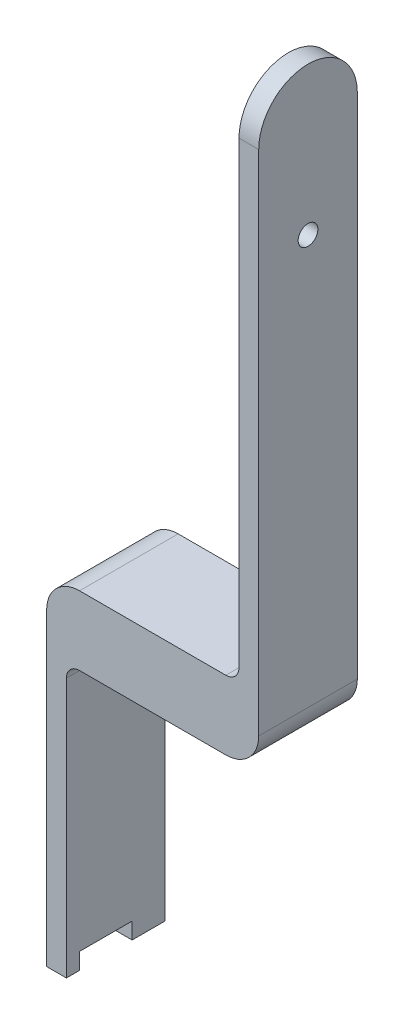
SolidWorks part; units mm, degrees
ref_plane "Front Plane" through (0, 0, 0) normal (0, 0, 1) x (1, 0, 0)
ref_plane "Top Plane" through (0, 0, 0) normal (0, 1, 0) x (1, 0, 0)
ref_plane "Right Plane" through (0, 0, 0) normal (1, 0, 0) x (0, 0, -1)
ref_plane "Plane1" through (-23.8759, 0, 0) normal (1, 0, 0) x (0, 0, -1)
sketch "Sketch1" plane through (-23.8759, 0, 0) normal (1, 0, 0) x (0, 0, -1)
  line L0 (-65.1937, 82.2511) -> (-65.1937, -41.5022)
  line L1 (-65.1937, -41.5022) -> (-50.1937, -41.5022)
  line L2 (-50.1937, -41.5022) -> (-50.1937, 82.2511)
  arc A0 (-50.1937, 82.2511) -> (-65.1937, 82.2511) centre (-57.6937, 82.2511) ccw
extrude "Boss-Extrude1" add sketch "Sketch1" against normal blind 32.2511
sketch "Sketch2" plane through (0, 0, 65.1937) normal (0, 0, 1) x (1, 0, 0)
  line L0 (-23.8759, -41.5022) -> (-23.8759, 0)
  line L1 (-23.8759, 0) -> (-53.127, 0)
  line L2 (-53.127, 0) -> (-53.127, -41.5022)
  line L3 (-53.127, -41.5022) -> (-23.8759, -41.5022)
extrude "Cut-Extrude1" cut sketch "Sketch2" against normal through all
sketch "Sketch3" plane through (0, 0, 65.1937) normal (0, 0, 1) x (1, 0, 0)
  line L0 (-56.127, 10.5) -> (-26.8759, 10.5)
  line L1 (-26.8759, 10.5) -> (-26.8759, 89.7511)
  line L2 (-26.8759, 89.7511) -> (-56.127, 89.7511)
  line L3 (-56.127, 89.7511) -> (-56.127, 10.5)
  line L4 (-23.8759, 89.7511) -> (-56.127, 89.7511) construction
extrude "Cut-Extrude2" cut sketch "Sketch3" against normal through all
sketch "Sketch4" plane through (-56.127, 0, 0) normal (-1, 0, 0) x (0, 0, 1)
  line L0 (55.1937, -41.5022) -> (63.1937, -41.5022)
  line L1 (63.1937, -41.5022) -> (63.1937, -39.0022)
  line L2 (63.1937, -39.0022) -> (55.1937, -39.0022)
  line L3 (55.1937, -39.0022) -> (55.1937, -41.5022)
extrude "Cut-Extrude3" cut sketch "Sketch4" against normal through all
hole_wizard "Ø3.0 (3) Diameter Hole1" positions "Sketch6" profile "Sketch5" hole size "Ø3.0" standard "ANSI Metric"
sketch "Sketch6" plane through (-23.8759, 0, 0) normal (1, 0, 0) x (0, 0, -1)
  point P0 (-57.6937, 67.2511)
sketch "Sketch5" plane through (-23.8759, 67.2511, 57.6937) normal (0, 1, 0) x (0, 0, -1)
  line L0 (0, 0) -> (0, 32.2511)
  line L1 (0, 32.2511) -> (1.5, 32.2511)
  line L2 (1.5, 32.2511) -> (1.5, 0)
  line L5 (1.5, 0) -> (0, 0)
  line L11 (0, -6.35) -> (0, 107.95) construction
  dimension "Thru Hole Dia." = 3
  dimension "Thru Hole Depth" = 32.2511
fillet "Fillet1" radius 2 2 edges at (-53.127, 0, 57.6937) (-26.8759, 10.5, 57.6937)
fillet "Fillet2" radius 5 2 edges at (-56.127, 10.5, 57.6937) (-23.8759, 0, 57.6937)
